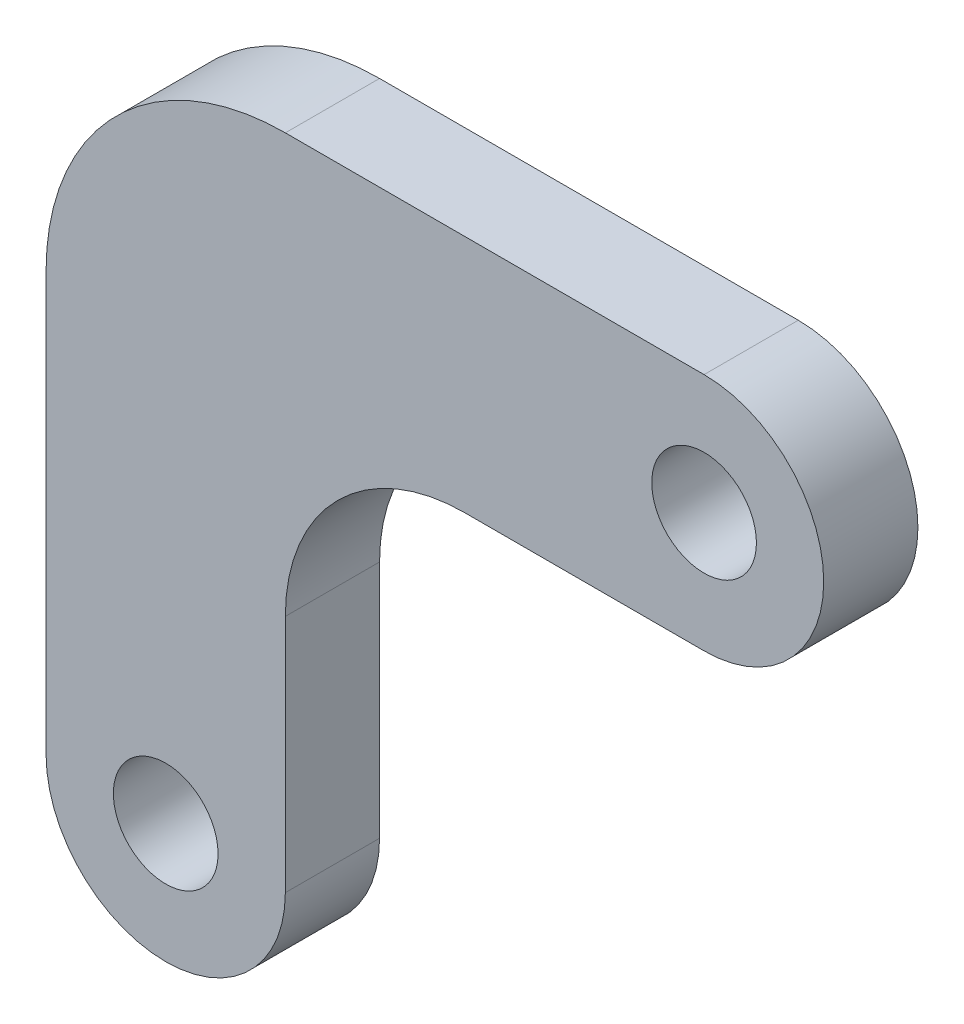
SolidWorks part; units mm, degrees
ref_plane "Front Plane" through (0, 0, 0) normal (0, 0, 1) x (1, 0, 0)
ref_plane "Top Plane" through (0, 0, 0) normal (0, 1, 0) x (1, 0, 0)
ref_plane "Right Plane" through (0, 0, 0) normal (1, 0, 0) x (0, 0, -1)
sketch "Sketch1" plane through (0, 0, 0) normal (0, 0, 1) x (1, 0, 0)
  line L0 (12.7, 69.85) -> (57.15, 69.85)
  line L2 (-12.7, 44.45) -> (-12.7, 0)
  line L4 (12.7, 25.4) -> (12.7, 0)
  line L6 (-12.7, 44.45) -> (-12.7, 0)
  line L7 (31.75, 44.45) -> (57.15, 44.45)
  arc A0 (-12.7, 0) -> (12.7, 0) centre (0, 0) ccw
  circle A1 centre (0, 0) radius 5.5563
  arc A2 (57.15, 44.45) -> (57.15, 69.85) centre (57.15, 57.15) ccw
  circle A3 centre (57.15, 57.15) radius 5.5562
  arc A4 (12.7, 25.4) -> (31.75, 44.45) centre (31.75, 25.4) cw
  arc A5 (-12.7, 44.45) -> (12.7, 69.85) centre (12.7, 44.45) cw
  dimension "D1" = 12.7
  dimension "D2" = 11.1125
  dimension "D4" = 11.1125
  dimension "D6" = 12.7
  dimension "D7" = 19.05
  dimension "D8" = 25.4
  dimension "D3" = 57.15
  dimension "D5" = 57.15
  dimension "D9" = 25.4
extrude "Boss-Extrude1" add sketch "Sketch1" along normal blind 10 contours A5 L2 A0 L4 A4 L7 A2 L0 A3 A1
